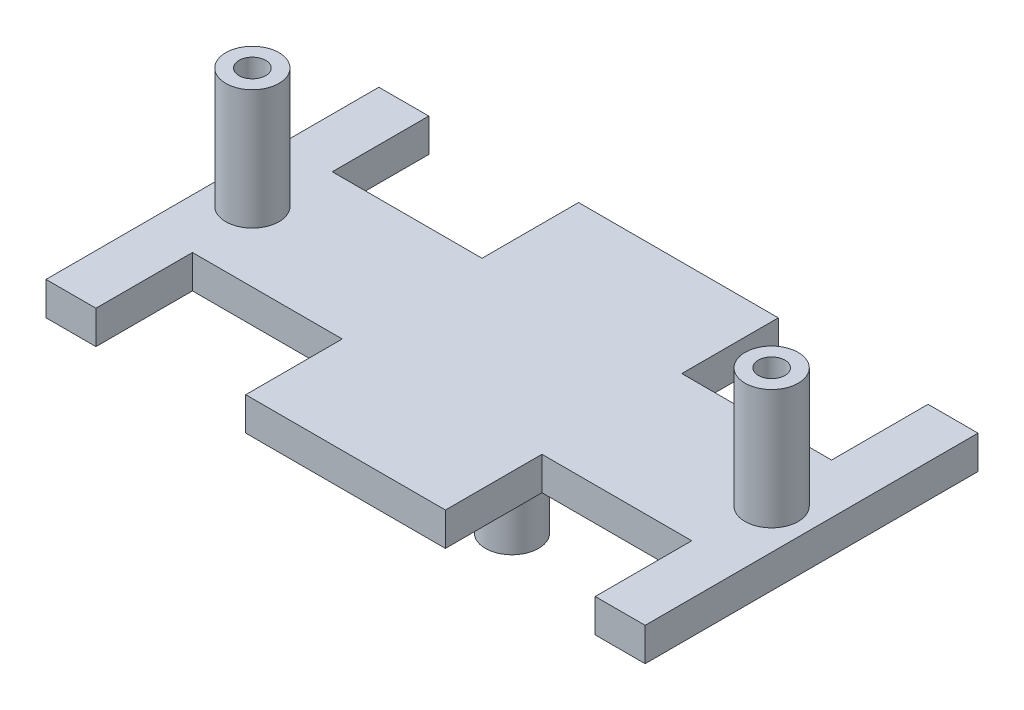
SolidWorks part; units mm, degrees
ref_plane "Front Plane" through (0, 0, 0) normal (0, 0, 1) x (1, 0, 0)
ref_plane "Top Plane" through (0, 0, 0) normal (0, 1, 0) x (1, 0, 0)
ref_plane "Right Plane" through (0, 0, 0) normal (1, 0, 0) x (0, 0, -1)
sketch "Sketch3" plane through (0, 0, 0) normal (0, 1, 0) x (1, 0, 0)
  line L1 (-119.5936, 38.9039) -> (-29.5936, 38.9039)
  line L2 (-119.5936, 38.9039) -> (-119.5936, -11.0961)
  line L3 (-119.5936, -11.0961) -> (-29.5936, -11.0961)
  line L4 (-29.5936, 38.9039) -> (-29.5936, -11.0961)
  line L5 (-119.5936, 38.9039) -> (-29.5936, -11.0961) construction
  line L6 (-119.5936, -11.0961) -> (-29.5936, 38.9039) construction
  point P0 (-74.5936, 13.9039)
  dimension "D1" = 90
  dimension "D2" = 50
extrude "Boss-Extrude1" add sketch "Sketch3" along normal blind 5
sketch "Sketch4" plane through (0, 5, 0) normal (0, 1, 0) x (1, 0, 0)
  line L0 (-90.0936, 24.4039) -> (-89.5936, 24.4039)
  line L7 (-89.5936, 24.4039) -> (-89.5936, 38.9039)
  line L9 (-29.5936, 38.9039) -> (-119.5936, 38.9039) construction
  line L11 (-89.5936, 38.9039) -> (-112.0936, 38.9039)
  line L13 (-112.0936, 24.4039) -> (-112.0936, 38.9039)
  line L32 (-112.0936, 24.4039) -> (-90.0936, 24.4039)
  point P0 (-74.4345, 14.391)
extrude "Cut-Extrude1" cut sketch "Sketch4" against normal blind 5
ref_plane "Plane1" through (-74.5936, 0, 0) normal (-1, 0, 0) x (0, 0, 1)
ref_plane "Plane2" through (0, 0, -13.9039) normal (0, 0, 1) x (1, 0, 0)
mirror "Mirror1" about plane through (0, 0, -13.9039) normal (0, 0, 1) of "Cut-Extrude1"
mirror "Mirror2" about plane through (-74.5936, 0, 0) normal (-1, 0, 0) of "Mirror1", "Cut-Extrude1"
sketch "Sketch5" plane through (0, 5, 0) normal (0, 1, 0) x (1, 0, 0)
  circle A0 centre (-35.5936, 13.9039) radius 4
extrude "Boss-Extrude2" add sketch "Sketch5" along normal blind 18
sketch "Sketch6" plane through (0, 23, 0) normal (0, 1, 0) x (1, 0, 0)
  circle A0 centre (-35.5936, 13.9039) radius 2
extrude "Cut-Extrude2" cut sketch "Sketch6" against normal blind 18
mirror "Mirror4" about plane through (-74.5936, 0, 0) normal (-1, 0, 0) of "Cut-Extrude2", "Boss-Extrude2"
sketch "Sketch8" plane through (0, 0, 0) normal (0, -1, 0) x (-1, 0, 0)
  circle A0 centre (74.5936, 13.9039) radius 4
extrude "Boss-Extrude3" add sketch "Sketch8" along normal blind 18
sketch "Sketch9" plane through (0, -18, 0) normal (0, -1, 0) x (-1, 0, 0)
  circle A0 centre (74.5936, 13.9039) radius 2
extrude "Cut-Extrude3" cut sketch "Sketch9" against normal blind 18
